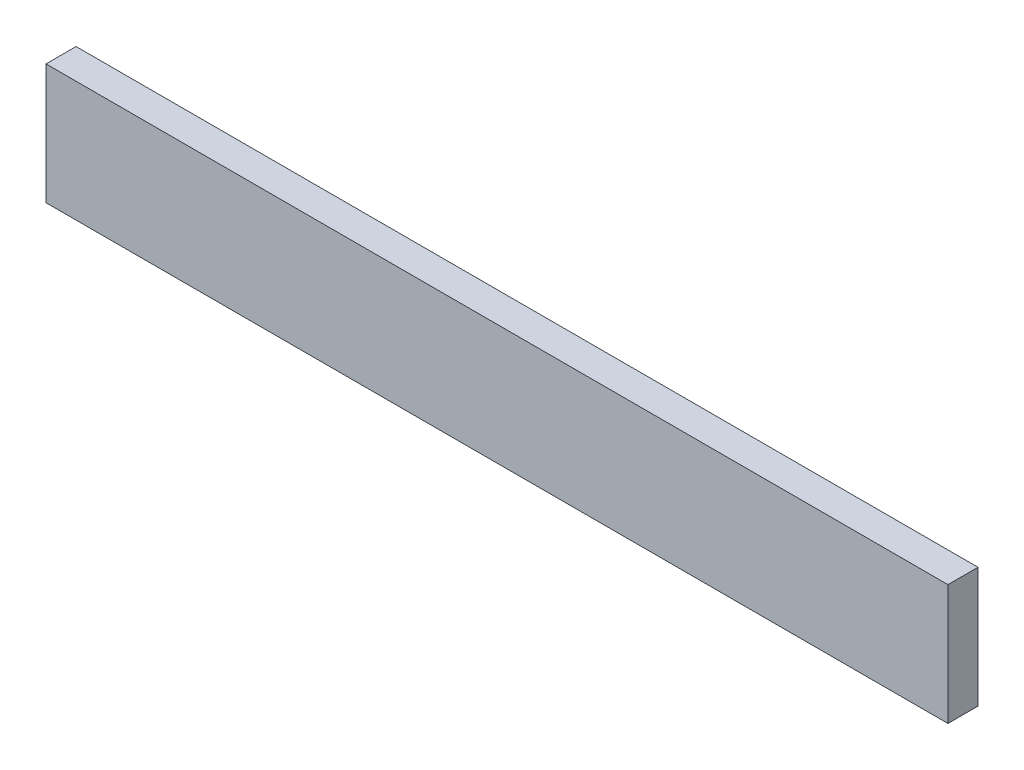
SolidWorks part; units mm, degrees
ref_plane "Front Plane" through (0, 0, 0) normal (0, 0, 1) x (1, 0, 0)
ref_plane "Top Plane" through (0, 0, 0) normal (0, 1, 0) x (1, 0, 0)
ref_plane "Right Plane" through (0, 0, 0) normal (1, 0, 0) x (0, 0, -1)
sketch "Sketch1" plane through (0, 0, 0) normal (0, 0, 1) x (1, 0, 0)
  line L1 (30, 4) -> (-30, 4)
  line L2 (30, 4) -> (30, -4)
  line L3 (30, -4) -> (-30, -4)
  line L4 (-30, 4) -> (-30, -4)
  line L5 (0, -4) -> (0, 4) construction
  line L6 (30, 0) -> (-30, 0) construction
  point P0 (0, 0)
  dimension "D1" = 60
  dimension "D2" = 8
extrude "Boss-Extrude1" add sketch "Sketch1" along normal mid plane 2
